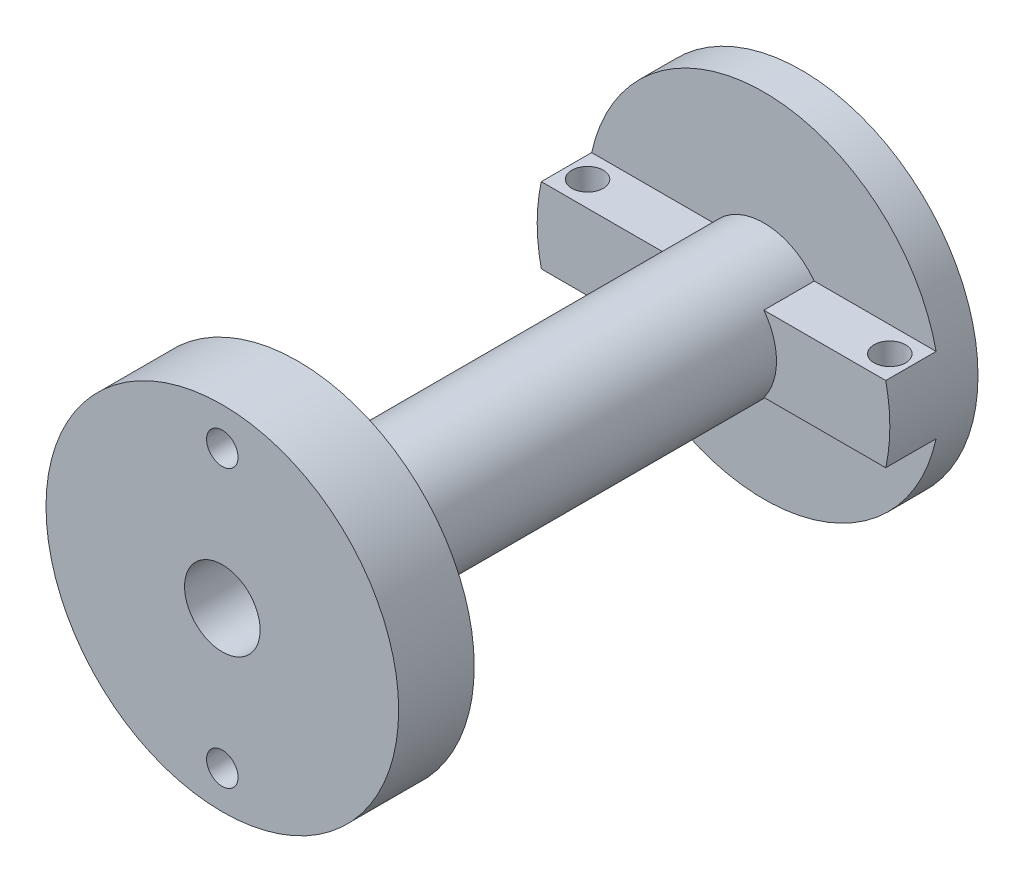
SolidWorks part; units mm, degrees
ref_plane "Front Plane" through (0, 0, 0) normal (0, 0, 1) x (1, 0, 0)
ref_plane "Top Plane" through (0, 0, 0) normal (0, 1, 0) x (1, 0, 0)
ref_plane "Right Plane" through (0, 0, 0) normal (1, 0, 0) x (0, 0, -1)
sketch "Sketch1" plane through (0, 0, 0) normal (0, 0, 1) x (1, 0, 0)
  circle A0 centre (0, 0) radius 7
  dimension "D1" = 14
extrude "Boss-Extrude1" add sketch "Sketch1" along normal blind 1.5
sketch "Sketch2" plane through (0, 0, 1.5) normal (0, 0, 1) x (1, 0, 0)
  circle A0 centre (0, 0) radius 2.5
  dimension "D1" = 5
extrude "Boss-Extrude2" add sketch "Sketch2" along normal blind 18.5
sketch "Sketch3" plane through (0, 0, 20) normal (0, 0, 1) x (1, 0, 0)
  circle A0 centre (0, 0) radius 7
  dimension "D1" = 14
extrude "Boss-Extrude3" add sketch "Sketch3" along normal blind 3
sketch "Sketch4" plane through (0, 0, 0) normal (0, 0, -1) x (-1, 0, 0)
  circle A0 centre (0, 0) radius 1.5
  dimension "D1" = 3
extrude "Cut-Extrude1" cut sketch "Sketch4" against normal up to next
sketch "Sketch5" plane through (0, 0, 23) normal (0, 0, 1) x (1, 0, 0)
  circle A0 centre (0, 5.5) radius 0.625
  circle A2 centre (0, -5.5) radius 0.625
extrude "Cut-Extrude4" cut sketch "Sketch5" against normal up to next
sketch "Sketch15" plane through (0, 0, 1.5) normal (0, 0, 1) x (1, 0, 0)
  line L1 (6.8374, -1.5) -> (-6.8374, -1.5)
  line L3 (6.8374, 1.5) -> (-6.8374, 1.5)
  line L5 (6.8374, -1.5) -> (-6.8374, 1.5) construction
  line L6 (6.8374, 1.5) -> (-6.8374, -1.5) construction
  arc A0 (6.8374, -1.5) -> (6.8374, 1.5) centre (0, 0) ccw
  circle A1 centre (0, 0) radius 7 construction
  arc A2 (-6.8374, 1.5) -> (-6.8374, -1.5) centre (0, 0) ccw
  point P0 (0, 0)
  point P6 (-6.8374, -1.5)
  dimension "D1" = 3
extrude "Boss-Extrude5" add sketch "Sketch15" along normal blind 2
sketch "Sketch16" plane through (0, -1.5, 0) normal (0, -1, 0) x (1, 0, 0)
  line L0 (-6.8374, 1.5) -> (-2, 1.5) construction
  line L1 (0, 0) -> (0, 18.3725) construction
  circle A0 centre (-6, 2.5) radius 0.625
  circle A1 centre (6, 2.5) radius 0.625
  dimension "D1" = 1.25
  dimension "D2" = 6
  dimension "D3" = 1
extrude "Cut-Extrude5" cut sketch "Sketch16" against normal up to next
sketch "Sketch17" plane through (0, 0, 1.5) normal (0, 0, -1) x (-1, 0, 0)
  circle A0 centre (0, 0) radius 1.5
extrude "Cut-Extrude6" cut sketch "Sketch17" against normal up to next
equation "\"15.5.000000mm\"=14"
